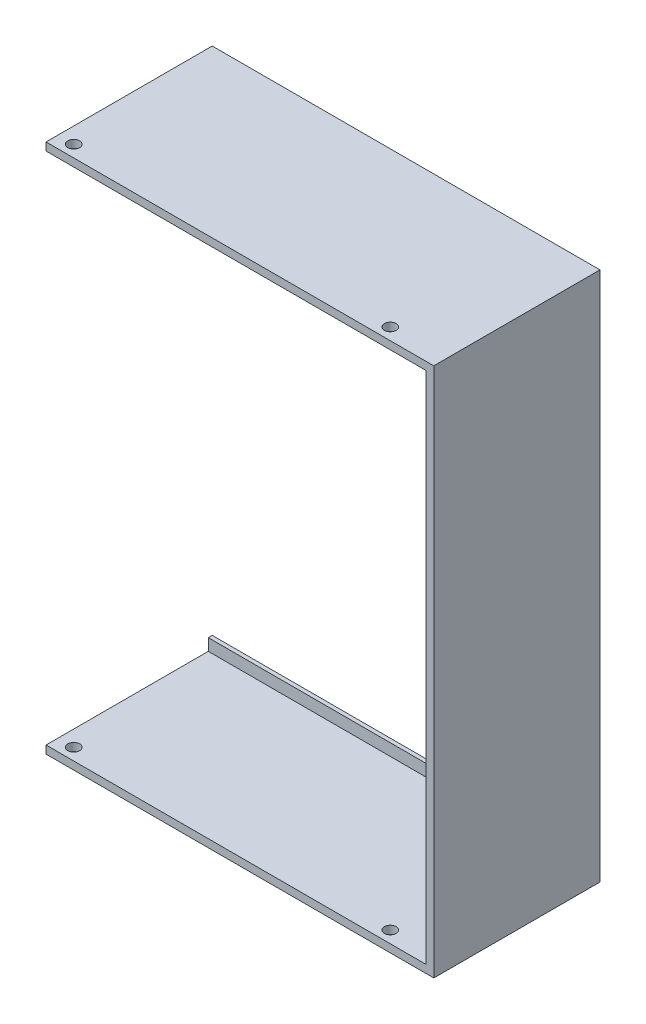
SolidWorks part; units mm, degrees
ref_plane "Front Plane" through (0, 0, 0) normal (0, 0, 1) x (1, 0, 0)
ref_plane "Top Plane" through (0, 0, 0) normal (0, 1, 0) x (1, 0, 0)
ref_plane "Right Plane" through (0, 0, 0) normal (1, 0, 0) x (0, 0, -1)
sketch "Sketch1" plane through (0, 0, 0) normal (0, 1, 0) x (1, 0, 0)
  line L1 (-4, -3) -> (94, -3)
  line L2 (-4, -3) -> (-4, 3)
  line L3 (-4, 3) -> (94, 3)
  line L4 (94, -3) -> (94, 3)
  circle A0 centre (0, 0) radius 1.5
  circle A1 centre (80, 0) radius 1.5
  dimension "D1" = 80
  dimension "D2" = 3
  dimension "D3" = 3
  dimension "D8" = 3
  dimension "D5" = 94
  dimension "D4" = 98
  dimension "D6" = 6
  dimension "D7" = 3
extrude "Boss-Extrude1" add sketch "Sketch1" along normal blind 2
sketch "Sketch2" plane through (0, 2, 0) normal (0, 1, 0) x (1, 0, 0)
  line L0 (-4, -3) -> (94, -3) construction
  line L1 (94, 3) -> (92, 3)
  line L2 (94, 3) -> (94, -3)
  line L3 (94, -3) -> (92, -3)
  line L4 (92, 3) -> (92, -3)
  dimension "D1" = 2
extrude "Boss-Extrude2" add sketch "Sketch2" along normal blind 130
sketch "Sketch3" plane through (0, 132, 0) normal (0, 1, 0) x (1, 0, 0)
  line L1 (94, -3) -> (-4, -3)
  line L2 (94, -3) -> (94, 3)
  line L3 (94, 3) -> (-4, 3)
  line L4 (-4, -3) -> (-4, 3)
  circle A0 centre (0, 0) radius 1.5
  circle A1 centre (80, 0) radius 1.5
extrude "Boss-Extrude3" add sketch "Sketch3" along normal blind 2
sketch "Sketch4" plane through (0, 0, -3) normal (0, 0, -1) x (-1, 0, 0)
  line L1 (4, 0) -> (-92, 0)
  line L2 (4, 0) -> (4, 2)
  line L3 (4, 2) -> (-92, 2)
  line L5 (4, 134) -> (-92, 134)
  line L6 (4, 134) -> (4, 132)
  line L7 (4, 132) -> (-92, 132)
  line L9 (-94, 134) -> (-92, 134)
  line L10 (-94, 134) -> (-94, 0)
  line L11 (-94, 0) -> (-92, 0)
  line L12 (-92, 132) -> (-92, 2)
extrude "Boss-Extrude4" add sketch "Sketch4" along normal blind 35
sketch "Sketch5" plane through (0, 0, -38) normal (0, 0, -1) x (-1, 0, 0)
  line L0 (-94, 134) -> (-94, 0) construction
  line L1 (4, 0) -> (-94, 0)
  line L2 (4, 0) -> (4, 5)
  line L3 (4, 5) -> (-89, 5)
  line L4 (-94, 0) -> (-94, 5)
  line L6 (4, 134) -> (-94, 134)
  line L7 (4, 134) -> (4, 129)
  line L8 (4, 129) -> (-89, 129)
  line L9 (-94, 134) -> (-94, 126)
  line L11 (-89, 129) -> (-89, 5)
  line L13 (-94, 126) -> (-94, 5)
  dimension "D1" = 5
  dimension "D2" = 5
  dimension "D3" = 5
extrude "Boss-Extrude5" add sketch "Sketch5" along normal blind 1
